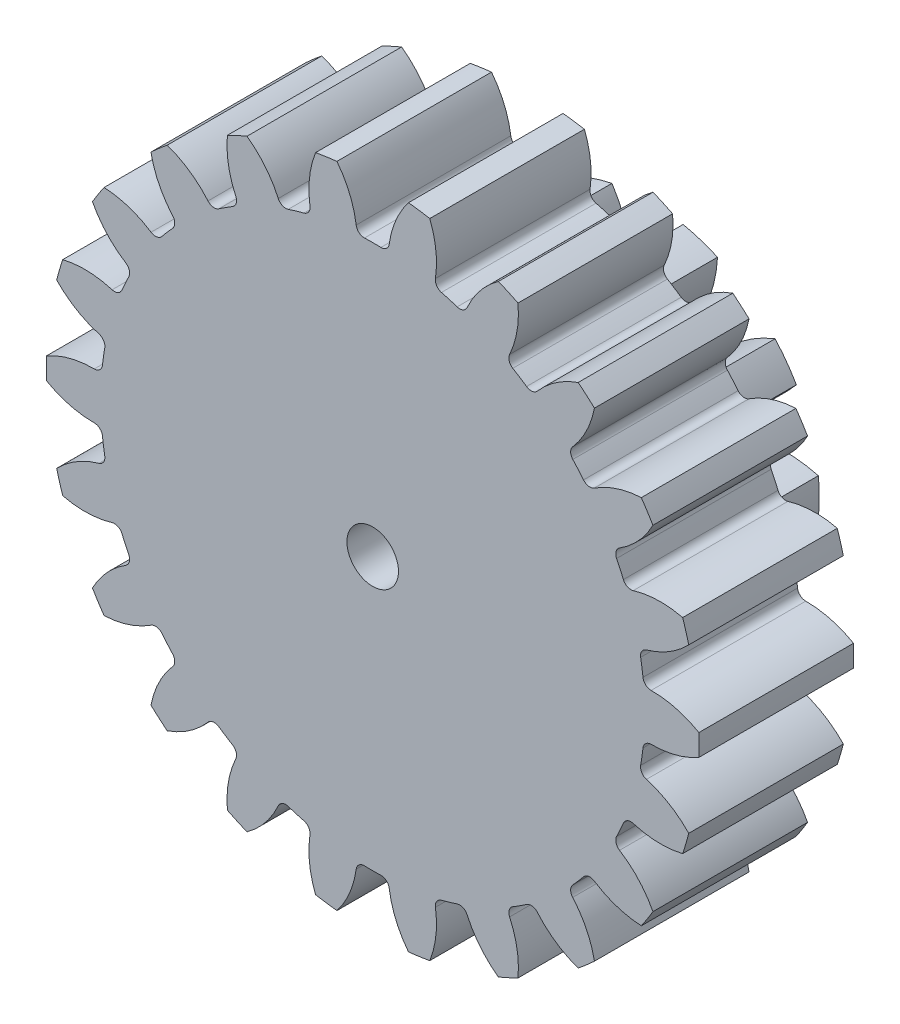
SolidWorks part; units mm, degrees
ref_plane "Front" through (0, 0, 0) normal (0, 0, 1) x (1, 0, 0)
ref_plane "Top" through (0, 0, 0) normal (0, 1, 0) x (1, 0, 0)
ref_plane "Right" through (0, 0, 0) normal (1, 0, 0) x (0, 0, -1)
sketch "Sketch1" plane through (0, 0, 0) normal (0, 0, 1) x (1, 0, 0)
  circle A0 centre (0, 0) radius 6.6667
  circle A1 centre (0, 0) radius 10
  circle A2 centre (0, 0) radius 8.3333
  dimension "D1" = 20
  dimension "D2" = 13.3333
  dimension "D3" = 16.6667
extrude "Boss-Extrude1" add sketch "Sketch1" along normal mid plane 7 contours A1
sketch "Sketch3" plane through (0, 0, 0) normal (0, 0, 1) x (1, 0, 0)
  line L0 (0, 0) -> (0, 10) construction
  line L1 (-1.3036, 8.2307) -> (1.3036, 8.2307) construction
  line L2 (-2.2285, 10.7719) -> (0, 4.6491) construction
  line L3 (0, 0) -> (3.0902, 9.5106) construction
  line L4 (1.3036, 8.2307) -> (3.7833, 7.4251) construction
  line L5 (0, 0) -> (-0.9018, 6.6054) construction
  circle A0 centre (0, 0) radius 10 construction
  arc A1 (-2.7219, 10.6579) -> (-0.9018, 6.6054) centre (-8.6908, 5.542) cw
  arc A2 (2.7219, 10.6579) -> (0.9018, 6.6054) centre (8.6908, 5.542) ccw
  arc A3 (0.9018, 6.6054) -> (-0.9018, 6.6054) centre (0, 0) ccw
  circle A4 centre (0, 0) radius 6.6667 construction
  circle A6 centre (0, 0) radius 8.3333 construction
  circle A7 centre (0, 0) radius 11
  arc A8 (2.7219, 10.6579) -> (-2.7219, 10.6579) centre (0, 0) ccw
  circle A9 centre (0, 0) radius 10 construction
  dimension "D3" = 18
  dimension "D2" = 20
extrude "Cut-Extrude1" cut sketch "Sketch3" against normal through all both and the other way through all
fillet "Fillet2" radius 0.5 2 edges at (0.9018, 6.6054, 0) (-0.9018, 6.6054, 0)
pattern_circular "CirPattern1" count 10 over 360 about axis through (0, 0, 0) along (0, 0, 1) of "Cut-Extrude1", "Fillet2"
sketch "Sketch4" plane through (0, 0, 3.5) normal (0, 0, 1) x (1, 0, 0)
  circle A0 centre (0, 0) radius 17.4167
  circle A1 centre (0, 0) radius 19
  circle A2 centre (0, 0) radius 15.8333
  dimension "D1" = 34.8333
  dimension "D2" = 38
  dimension "D3" = 31.6667
extrude "Boss-Extrude2" add sketch "Sketch4" along normal blind 9 separate body
sketch "Sketch5" plane through (0, 0, 12.5) normal (0, 0, 1) x (1, 0, 0)
  line L0 (0, 0) -> (0, 19) construction
  line L1 (-1.2425, 17.3723) -> (1.2425, 17.3723) construction
  line L2 (-0.9193, 15.8066) -> (0, 0) construction
  line L3 (-2.1565, 19.8834) -> (0, 13.9586) construction
  line L4 (0, 0) -> (2.704, 18.8066) construction
  line L5 (1.2425, 17.3723) -> (3.7022, 17.0186) construction
  circle A0 centre (0, 0) radius 19 construction
  arc A1 (-2.9634, 19.7792) -> (-0.9193, 15.8066) centre (-6.4237, 15.4865) cw
  arc A2 (2.9634, 19.7792) -> (0.9193, 15.8066) centre (6.4237, 15.4865) ccw
  circle A3 centre (0, 0) radius 15.8333 construction
  arc A4 (0.9193, 15.8066) -> (-0.9193, 15.8066) centre (0, 0) ccw
  circle A6 centre (0, 0) radius 17.4167 construction
  circle A7 centre (0, 0) radius 20
  arc A8 (2.9634, 19.7792) -> (-2.9634, 19.7792) centre (0, 0) ccw
  circle A9 centre (0, 0) radius 19 construction
  dimension "D2" = 20
  dimension "D3" = 8.182
extrude "Cut-Extrude2" cut sketch "Sketch5" against normal up to surface (9 mm away) up to face at (19, 0, 3.5)
fillet "Fillet3" radius 0.475 2 edges at (0.9193, 15.8066, 8) (-0.9193, 15.8066, 8)
pattern_circular "CirPattern2" count 22 over 360 about axis through (0, 0, 0) along (0, 0, 1) of "Cut-Extrude2", "Fillet3"
sketch "Sketch6" plane through (0, 0, 12.5) normal (0, 0, 1) x (1, 0, 0)
  circle A0 centre (0, 0) radius 1.5
  dimension "D1" = 3
extrude "Cut-Extrude3" cut sketch "Sketch6" against normal through all
equation "\"bot_n\"= 10'bottom number of teeth"
equation "\"bot_m\"= \"bot_od\" / ( \"bot_n\" + 2 )'bottom module"
equation "\"bot_p\"= \"bot_m\" * pi'bottom pitch"
equation "\"bot_d\"= \"bot_m\" * \"bot_n\"'bottom primitive diameter"
equation "\"bot_da\"= \"bot_d\" + 2 * \"bot_m\"'bottom head diamater"
equation "\"bot_df\"= \"bot_d\" - 2 * \"bot_m\"'bottom foot diameter"
equation "\"bot_od\"= 20'bottom outer diameter"
equation "\"D1@Sketch1\"=\"bot_od\""
equation "\"D2@Sketch1\"=\"bot_df\""
equation "\"D3@Sketch1\"=\"bot_d\""
equation "\"D3@Sketch3\"= 180 / \"bot_n\""
equation "\"D1@Fillet2\"=.3*\"bot_m\""
equation "\"top_n\"= 22'top number of teeth"
equation "\"top_od\"= 38'top outer diameter"
equation "\"top_m\"= \"top_od\" / ( \"top_n\" + 2 )'top module"
equation "\"top_p\"= \"top_m\" * pi'top pitch"
equation "\"top_d\"= \"top_m\" * \"top_n\"'top primitive diameter"
equation "\"top_da\"= \"top_d\" + 2 * \"top_m\"'top head diameter"
equation "\"top_df\"= \"top_d\" - 2 * \"top_m\"'top foot diamter"
equation "\"D1@CirPattern1\"= \"bot_n\""
equation "\"D1@Sketch4\"= \"top_m\" * \"top_n\""
equation "\"D2@Sketch4\"= (\"top_n\" + 2) * \"top_m\""
equation "\"D3@Sketch4\"=\"top_df\""
equation "\"D3@Sketch5\"= 180 / \"top_n\""
equation "\"D1@Fillet3\"=.3 * \"top_m\""
equation "\"D1@CirPattern2\"= \"top_n\""
